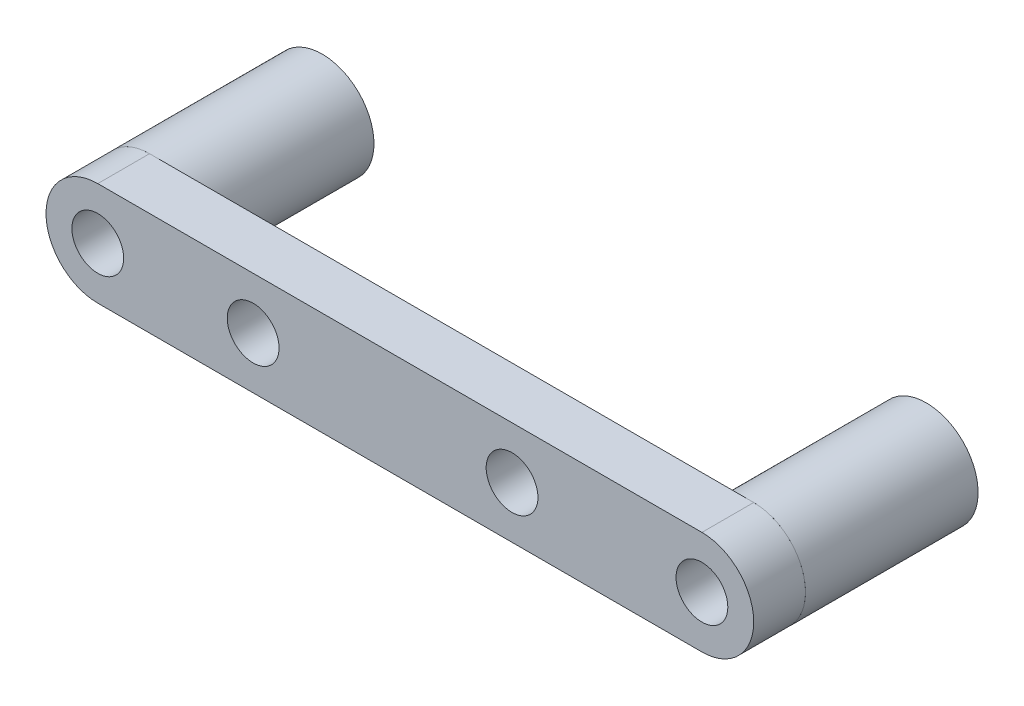
SolidWorks part; units mm, degrees
material "ﾎﾟﾘｵｷｼﾒﾁﾚﾝ(POM)ｱｾﾀｰﾙ共重合体"
ref_plane "正面" through (0, 0, 0) normal (0, 0, 1) x (1, 0, 0)
ref_plane "平面" through (0, 0, 0) normal (0, 1, 0) x (1, 0, 0)
ref_plane "右側面" through (0, 0, 0) normal (1, 0, 0) x (0, 0, -1)
sketch "ｽｹｯﾁ1" plane through (0, 0, 0) normal (0, 0, 1) x (1, 0, 0)
  line L0 (-7.5, 0) -> (7.5, 0) construction
  line L1 (-7.5, 3) -> (7.5, 3)
  line L2 (-7.5, -3) -> (7.5, -3)
  arc A0 (-7.5, 3) -> (-7.5, -3) centre (-7.5, 0) ccw
  arc A1 (7.5, -3) -> (7.5, 3) centre (7.5, 0) ccw
  circle A2 centre (-7.5, 0) radius 1.5
  circle A3 centre (7.5, 0) radius 1.5
  point P2 (0, 0)
  dimension "D1" = 3
  dimension "D3" = 3
  dimension "D2" = 15
extrude "ﾎﾞｽ - 押し出し1" add sketch "ｽｹｯﾁ1" along normal blind 3
sketch "ｽｹｯﾁ2" plane through (0, 0, 3) normal (0, 0, 1) x (1, 0, 0)
  line L0 (-7.5, 3) -> (-16.5, 3)
  line L1 (-7.5, -3) -> (-16.5, -3)
  line L2 (7.5, 3) -> (18.5, 3)
  line L4 (7.5, -3) -> (18.5, -3)
  arc A0 (-16.5, 3) -> (-16.5, -3) centre (-16.5, 0) ccw
  arc A1 (-7.5, 3) -> (-7.5, -3) centre (-7.5, 0) ccw construction
  arc A2 (-7.5, 3) -> (-7.5, -3) centre (-7.5, 0) ccw
  circle A3 centre (-16.5, 0) radius 1.5
  arc A4 (7.5, -3) -> (7.5, 3) centre (7.5, 0) ccw construction
  arc A5 (7.5, -3) -> (7.5, 3) centre (7.5, 0) ccw
  arc A6 (18.5, 3) -> (18.5, -3) centre (18.5, 0) cw
  circle A7 centre (18.5, 0) radius 1.5
  circle A8 centre (7.5, 0) radius 1.5 construction
  dimension "D1" = 9
  dimension "D2" = 3
  dimension "D3" = 11
extrude "ﾎﾞｽ - 押し出し2" add sketch "ｽｹｯﾁ2" against normal up to surface (3 mm away) up to face at (0, 0, 0)
sketch "ｽｹｯﾁ3" plane through (0, 0, 0) normal (0, 0, -1) x (-1, 0, 0)
  circle A0 centre (16.5, 0) radius 1.5
  circle A1 centre (16.5, 0) radius 3
  circle A2 centre (-18.5, 0) radius 1.5 construction
  circle A3 centre (-18.5, 0) radius 1.5
  circle A4 centre (-18.5, 0) radius 3
  dimension "D1" = 3
  dimension "D2" = 6
extrude "ﾎﾞｽ - 押し出し3" add sketch "ｽｹｯﾁ3" along normal blind 10 separate body
